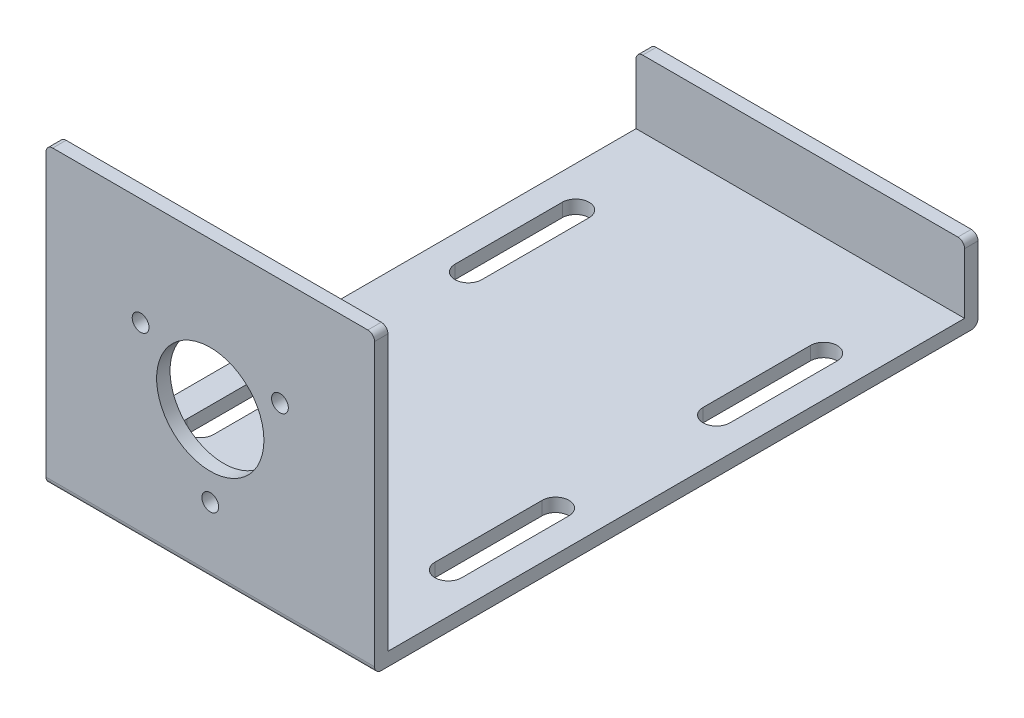
SolidWorks part; units mm, degrees
ref_plane "Front Plane" through (0, 0, 0) normal (0, 0, 1) x (1, 0, 0)
ref_plane "Top Plane" through (0, 0, 0) normal (0, 1, 0) x (1, 0, 0)
ref_plane "Right Plane" through (0, 0, 0) normal (1, 0, 0) x (0, 0, -1)
sketch "Sketch3" plane through (0, 0, 0) normal (1, 0, 0) x (0, 0, -1)
  line L0 (0, 0) -> (2, 0)
  line L1 (2, 0) -> (2, -42)
  line L2 (2, -42) -> (88, -42)
  line L3 (88, -42) -> (88, -32)
  line L4 (88, -32) -> (90, -32)
  line L5 (90, -32) -> (90, -44)
  line L6 (90, -44) -> (0, -44)
  line L7 (0, -44) -> (0, 0)
  line L8 (0, 0) -> (-0.0588, -0.1471)
  dimension "D1" = 2
  dimension "D2" = 44
  dimension "D3" = 90
  dimension "D4" = 2
  dimension "D5" = 12
  dimension "D6" = 42
extrude "Boss-Extrude2" add sketch "Sketch3" along normal blind 49 contours L0 L1 L2 L3 L4 L5 L6 L7
sketch "Sketch4" plane through (0, 0, 0) normal (0, 0, 1) x (1, 0, 0)
  line L0 (0, -44) -> (24.5, -44) construction
  line L1 (24.5, -44) -> (24.5, -34) construction
  line L2 (24.5, -34) -> (24.5, -22) construction
  line L3 (24.5, -22) -> (14.1077, -16) construction
  line L4 (24.5, -22) -> (34.8923, -16) construction
  circle A0 centre (24.5, -22) radius 12 construction
  circle A1 centre (24.5, -34) radius 1.25
  circle A2 centre (14.1077, -16) radius 1.25
  circle A3 centre (34.8923, -16) radius 1.25
  circle A4 centre (24.5, -22) radius 8
  dimension "D4" = 120
  dimension "D6" = 2.5
  dimension "D7" = 2.5
  dimension "D8" = 2.5
  dimension "D9" = 16
  dimension "D1" = 24.5
  dimension "D2" = 10
  dimension "D3" = 12
  dimension "D5" = 120
extrude "Cut-Extrude1" cut sketch "Sketch4" against normal up to next
sketch "Sketch5" plane through (0, -44, 0) normal (0, -1, 0) x (1, 0, 0)
  line L0 (49, 0) -> (43, 0) construction
  line L1 (49, 0) -> (0, 0) construction
  line L2 (43, 0) -> (43, -17) construction
  line L3 (43, -17) -> (43, -33) construction
  line L4 (41, -17) -> (41, -33)
  line L5 (45, -17) -> (45, -33)
  line L6 (43, -35) -> (43, -55) construction
  line L7 (43, -45) -> (38.1628, -45) construction
  line L8 (45, -73) -> (45, -57)
  line L9 (41, -73) -> (41, -57)
  line L10 (24.5, 0) -> (24.5, -77.8924) construction
  line L11 (6, -45) -> (10.8372, -45) construction
  line L12 (6, -35) -> (6, -55) construction
  line L13 (6, -17) -> (6, -33) construction
  line L14 (8, -73) -> (8, -57)
  line L15 (4, -73) -> (4, -57)
  line L16 (4, -17) -> (4, -33)
  line L17 (8, -17) -> (8, -33)
  arc A0 (45, -17) -> (41, -17) centre (43, -17) ccw
  arc A1 (41, -33) -> (45, -33) centre (43, -33) ccw
  arc A2 (41, -57) -> (45, -57) centre (43, -57) cw
  arc A3 (45, -73) -> (41, -73) centre (43, -73) cw
  arc A4 (4, -73) -> (8, -73) centre (6, -73) ccw
  arc A5 (8, -57) -> (4, -57) centre (6, -57) ccw
  arc A6 (8, -33) -> (4, -33) centre (6, -33) cw
  arc A7 (4, -17) -> (8, -17) centre (6, -17) cw
  dimension "D3" = 4
  dimension "D4" = 4
  dimension "D1" = 6
  dimension "D2" = 17
  dimension "D5" = 16
  dimension "D6" = 10
extrude "Cut-Extrude3" cut sketch "Sketch5" against normal up to next
fillet "Fillet2" radius 1 6 edges at (0, -32, -89) (49, -32, -89) (49, 0, -1) (0, 0, -1) (24.5, -44, 0) (24.5, -44, -90)
